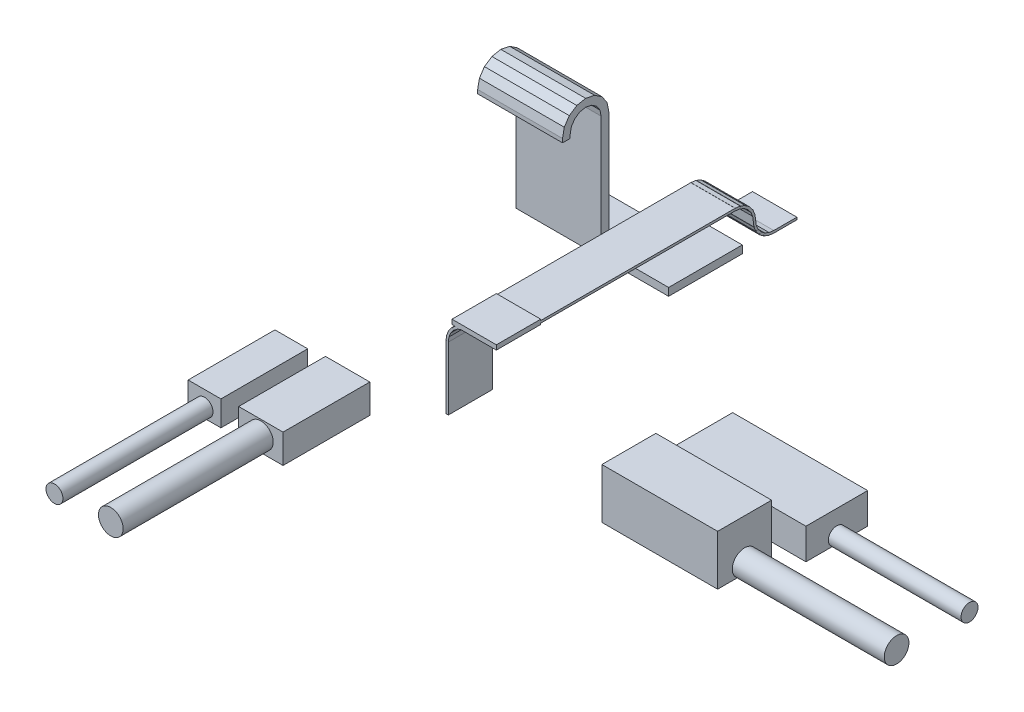
SolidWorks part; units mm, degrees
ref_plane "Front Plane" through (0, 0, 0) normal (0, 0, 1) x (1, 0, 0)
ref_plane "Top Plane" through (0, 0, 0) normal (0, 1, 0) x (1, 0, 0)
ref_plane "Right Plane" through (0, 0, 0) normal (1, 0, 0) x (0, 0, -1)
ref_plane "PY93" through (0, 0, 93) normal (0, 0, 1) x (1, 0, 0)
sketch "Sketch1" plane through (0, 0, 93) normal (0, 0, 1) x (1, 0, 0)
  line L0 (-48.05, -16.05) -> (-39.55, -16.05)
  line L1 (-39.55, -16.05) -> (-39.55, -9.55)
  line L2 (-39.55, -9.55) -> (-48.05, -9.55)
  line L3 (-48.05, -9.55) -> (-48.05, -16.05)
extrude "Plug usbc" add sketch "Sketch1" along normal blind 22.5
ref_plane "PY115" through (0, 0, 115) normal (0, 0, 1) x (1, 0, 0)
sketch "Sketch2" plane through (0, 0, 115) normal (0, 0, 1) x (1, 0, 0)
  circle A0 centre (-43.8, -13.5) radius 2.2
extrude "Cable usbc" add sketch "Sketch2" along normal blind 39.4
sketch "Sketch3" plane through (0, 0, 93) normal (0, 0, 1) x (1, 0, 0)
  line L0 (-34.95, -16.45) -> (-23.45, -16.45)
  line L1 (-23.45, -16.45) -> (-23.45, -8.95)
  line L2 (-23.45, -8.95) -> (-34.95, -8.95)
  line L3 (-34.95, -8.95) -> (-34.95, -16.45)
extrude "Plug hdmi" add sketch "Sketch3" along normal blind 22.5
sketch "Sketch4" plane through (0, 0, 115) normal (0, 0, 1) x (1, 0, 0)
  circle A0 centre (-29.2, -12.5) radius 3.2
extrude "Cable hdmi" add sketch "Sketch4" along normal blind 39.4
ref_plane "PX33" through (33, 0, 0) normal (1, 0, 0) x (0, 0, -1)
sketch "Sketch5" plane through (33, 0, 0) normal (1, 0, 0) x (0, 0, -1)
  line L0 (-89.3, -14.1) -> (-75.3, -14.1)
  line L1 (-75.3, -14.1) -> (-75.3, -1.1)
  line L2 (-75.3, -1.1) -> (-89.3, -1.1)
  line L3 (-89.3, -1.1) -> (-89.3, -14.1)
extrude "Plug eth" add sketch "Sketch5" along normal blind 30
ref_plane "PX62_5" through (62.5, 0, 0) normal (1, 0, 0) x (0, 0, -1)
sketch "Sketch6" plane through (62.5, 0, 0) normal (1, 0, 0) x (0, 0, -1)
  circle A0 centre (-82.3, -11.5) radius 3.2
extrude "Cable eth" add sketch "Sketch6" along normal blind 39.9
sketch "Sketch7" plane through (33, 0, 0) normal (1, 0, 0) x (0, 0, -1)
  line L0 (-71.4, -14.4) -> (-55.4, -14.4)
  line L1 (-55.4, -14.4) -> (-55.4, -6.4)
  line L2 (-55.4, -6.4) -> (-71.4, -6.4)
  line L3 (-71.4, -6.4) -> (-71.4, -14.4)
extrude "Plug usba" add sketch "Sketch7" along normal blind 35
ref_plane "PX67_5" through (67.5, 0, 0) normal (1, 0, 0) x (0, 0, -1)
sketch "Sketch8" plane through (67.5, 0, 0) normal (1, 0, 0) x (0, 0, -1)
  circle A0 centre (-63.4, -12.5) radius 2.2
extrude "Cable usba" add sketch "Sketch8" along normal blind 34.9
ref_plane "PXm5_35" through (-5.35, 0, 0) normal (1, 0, 0) x (0, 0, -1)
sketch "Sketch9" plane through (-5.35, 0, 0) normal (1, 0, 0) x (0, 0, -1)
  line L0 (-11.9, 1.7) -> (-17.9, 1.7)
  line L1 (-17.9, 1.7) -> (-17.9, 2.3)
  line L2 (-17.9, 2.3) -> (-11.9, 2.3)
  line L3 (-11.9, 2.3) -> (-11.9, 1.7)
extrude "Ribbon 0" add sketch "Sketch9" along normal blind 11.5
sketch "Sketch10" plane through (-5.35, 0, 0) normal (1, 0, 0) x (0, 0, -1)
  line L0 (-17.9392, 1.7026) -> (-19.2333, 1.8729)
  line L1 (-19.2333, 1.8729) -> (-19.1549, 2.4678)
  line L2 (-19.1549, 2.4678) -> (-17.8608, 2.2974)
  line L3 (-17.8608, 2.2974) -> (-17.9392, 1.7026)
extrude "Ribbon 1" add sketch "Sketch10" along normal blind 11.5
sketch "Sketch11" plane through (-5.35, 0, 0) normal (1, 0, 0) x (0, 0, -1)
  line L0 (-19.3089, 1.8932) -> (-20.5148, 2.3927)
  line L1 (-20.5148, 2.3927) -> (-20.2852, 2.947)
  line L2 (-20.2852, 2.947) -> (-19.0793, 2.4475)
  line L3 (-19.0793, 2.4475) -> (-19.3089, 1.8932)
extrude "Ribbon 2" add sketch "Sketch11" along normal blind 11.5
sketch "Sketch12" plane through (-5.35, 0, 0) normal (1, 0, 0) x (0, 0, -1)
  line L0 (-20.5826, 2.4319) -> (-21.6182, 3.2265)
  line L1 (-21.6182, 3.2265) -> (-21.2529, 3.7025)
  line L2 (-21.2529, 3.7025) -> (-20.2174, 2.9079)
  line L3 (-20.2174, 2.9079) -> (-20.5826, 2.4319)
extrude "Ribbon 3" add sketch "Sketch12" along normal blind 11.5
sketch "Sketch13" plane through (-5.35, 0, 0) normal (1, 0, 0) x (0, 0, -1)
  line L0 (-21.6735, 3.2818) -> (-22.4681, 4.3174)
  line L1 (-22.4681, 4.3174) -> (-21.9921, 4.6826)
  line L2 (-21.9921, 4.6826) -> (-21.1975, 3.6471)
  line L3 (-21.1975, 3.6471) -> (-21.6735, 3.2818)
extrude "Ribbon 4" add sketch "Sketch13" along normal blind 11.5
sketch "Sketch14" plane through (-5.35, 0, 0) normal (1, 0, 0) x (0, 0, -1)
  line L0 (-22.5073, 4.3852) -> (-23.0068, 5.5911)
  line L1 (-23.0068, 5.5911) -> (-22.4525, 5.8207)
  line L2 (-22.4525, 5.8207) -> (-21.953, 4.6148)
  line L3 (-21.953, 4.6148) -> (-22.5073, 4.3852)
extrude "Ribbon 5" add sketch "Sketch14" along normal blind 11.5
sketch "Sketch15" plane through (-5.35, 0, 0) normal (1, 0, 0) x (0, 0, -1)
  line L0 (-23.0271, 5.6667) -> (-23.1974, 6.9608)
  line L1 (-23.1974, 6.9608) -> (-22.6026, 7.0392)
  line L2 (-22.6026, 7.0392) -> (-22.4322, 5.7451)
  line L3 (-22.4322, 5.7451) -> (-23.0271, 5.6667)
extrude "Ribbon 6" add sketch "Sketch15" along normal blind 11.5
sketch "Sketch16" plane through (-5.35, 0, 0) normal (1, 0, 0) x (0, 0, -1)
  line L0 (-23.1974, 6.9608) -> (-23.3678, 8.2549)
  line L1 (-23.3678, 8.2549) -> (-22.7729, 8.3333)
  line L2 (-22.7729, 8.3333) -> (-22.6026, 7.0392)
  line L3 (-22.6026, 7.0392) -> (-23.1974, 6.9608)
extrude "Ribbon 7" add sketch "Sketch16" along normal blind 11.5
sketch "Sketch17" plane through (-5.35, 0, 0) normal (1, 0, 0) x (0, 0, -1)
  line L0 (-23.3475, 8.1793) -> (-23.847, 9.3852)
  line L1 (-23.847, 9.3852) -> (-23.2927, 9.6148)
  line L2 (-23.2927, 9.6148) -> (-22.7932, 8.4089)
  line L3 (-22.7932, 8.4089) -> (-23.3475, 8.1793)
extrude "Ribbon 8" add sketch "Sketch17" along normal blind 11.5
sketch "Sketch18" plane through (-5.35, 0, 0) normal (1, 0, 0) x (0, 0, -1)
  line L0 (-23.8079, 9.3174) -> (-24.6025, 10.3529)
  line L1 (-24.6025, 10.3529) -> (-24.1265, 10.7182)
  line L2 (-24.1265, 10.7182) -> (-23.3319, 9.6826)
  line L3 (-23.3319, 9.6826) -> (-23.8079, 9.3174)
extrude "Ribbon 9" add sketch "Sketch18" along normal blind 11.5
sketch "Sketch19" plane through (-5.35, 0, 0) normal (1, 0, 0) x (0, 0, -1)
  line L0 (-24.5471, 10.2975) -> (-25.5826, 11.0921)
  line L1 (-25.5826, 11.0921) -> (-25.2174, 11.5681)
  line L2 (-25.2174, 11.5681) -> (-24.1818, 10.7735)
  line L3 (-24.1818, 10.7735) -> (-24.5471, 10.2975)
extrude "Ribbon 10" add sketch "Sketch19" along normal blind 11.5
sketch "Sketch20" plane through (-5.35, 0, 0) normal (1, 0, 0) x (0, 0, -1)
  line L0 (-25.5148, 11.053) -> (-26.7207, 11.5525)
  line L1 (-26.7207, 11.5525) -> (-26.4911, 12.1068)
  line L2 (-26.4911, 12.1068) -> (-25.2852, 11.6073)
  line L3 (-25.2852, 11.6073) -> (-25.5148, 11.053)
extrude "Ribbon 11" add sketch "Sketch20" along normal blind 11.5
sketch "Sketch21" plane through (-5.35, 0, 0) normal (1, 0, 0) x (0, 0, -1)
  line L0 (-26.6451, 11.5322) -> (-27.9392, 11.7026)
  line L1 (-27.9392, 11.7026) -> (-27.8608, 12.2974)
  line L2 (-27.8608, 12.2974) -> (-26.5667, 12.1271)
  line L3 (-26.5667, 12.1271) -> (-26.6451, 11.5322)
extrude "Ribbon 12" add sketch "Sketch21" along normal blind 11.5
sketch "Sketch22" plane through (-5.35, 0, 0) normal (1, 0, 0) x (0, 0, -1)
  line L0 (-27.9, 11.7) -> (-84.05, 11.7)
  line L1 (-84.05, 11.7) -> (-84.05, 12.3)
  line L2 (-84.05, 12.3) -> (-27.9, 12.3)
  line L3 (-27.9, 12.3) -> (-27.9, 11.7)
extrude "Ribbon 13" add sketch "Sketch22" along normal blind 11.5
ref_plane "PZ11_4" through (0, 11.4, 0) normal (0, 1, 0) x (1, 0, 0)
sketch "Sketch23" plane through (0, 11.4, 0) normal (0, 1, 0) x (1, 0, 0)
  line L0 (-5.35, -89.8) -> (6.15, -89.8)
  line L1 (6.15, -89.8) -> (6.15, -78.3)
  line L2 (6.15, -78.3) -> (-5.35, -78.3)
  line L3 (-5.35, -78.3) -> (-5.35, -89.8)
extrude "Ribbon Fold" add sketch "Sketch23" along normal blind 1.2
ref_plane "PY78_3" through (0, 0, 78.3) normal (0, 0, 1) x (1, 0, 0)
sketch "Sketch24" plane through (0, 0, 78.3) normal (0, 0, 1) x (1, 0, 0)
  line L0 (0.4, 11.7) -> (-1.6, 11.7)
  line L1 (-1.6, 11.7) -> (-1.6, 12.3)
  line L2 (-1.6, 12.3) -> (0.4, 12.3)
  line L3 (0.4, 12.3) -> (0.4, 11.7)
extrude "Ribbon 14" add sketch "Sketch24" along normal blind 11.5
sketch "Sketch25" plane through (0, 0, 78.3) normal (0, 0, 1) x (1, 0, 0)
  line L0 (-1.5608, 11.7026) -> (-2.8549, 11.5322)
  line L1 (-2.8549, 11.5322) -> (-2.9333, 12.1271)
  line L2 (-2.9333, 12.1271) -> (-1.6392, 12.2974)
  line L3 (-1.6392, 12.2974) -> (-1.5608, 11.7026)
extrude "Ribbon 15" add sketch "Sketch25" along normal blind 11.5
sketch "Sketch26" plane through (0, 0, 78.3) normal (0, 0, 1) x (1, 0, 0)
  line L0 (-2.7793, 11.5525) -> (-3.9852, 11.053)
  line L1 (-3.9852, 11.053) -> (-4.2148, 11.6073)
  line L2 (-4.2148, 11.6073) -> (-3.0089, 12.1068)
  line L3 (-3.0089, 12.1068) -> (-2.7793, 11.5525)
extrude "Ribbon 16" add sketch "Sketch26" along normal blind 11.5
sketch "Sketch27" plane through (0, 0, 78.3) normal (0, 0, 1) x (1, 0, 0)
  line L0 (-3.9174, 11.0921) -> (-4.9529, 10.2975)
  line L1 (-4.9529, 10.2975) -> (-5.3182, 10.7735)
  line L2 (-5.3182, 10.7735) -> (-4.2826, 11.5681)
  line L3 (-4.2826, 11.5681) -> (-3.9174, 11.0921)
extrude "Ribbon 17" add sketch "Sketch27" along normal blind 11.5
sketch "Sketch28" plane through (0, 0, 78.3) normal (0, 0, 1) x (1, 0, 0)
  line L0 (-4.8975, 10.3529) -> (-5.6921, 9.3174)
  line L1 (-5.6921, 9.3174) -> (-6.1681, 9.6826)
  line L2 (-6.1681, 9.6826) -> (-5.3735, 10.7182)
  line L3 (-5.3735, 10.7182) -> (-4.8975, 10.3529)
extrude "Ribbon 18" add sketch "Sketch28" along normal blind 11.5
sketch "Sketch29" plane through (0, 0, 78.3) normal (0, 0, 1) x (1, 0, 0)
  line L0 (-5.653, 9.3852) -> (-6.1525, 8.1793)
  line L1 (-6.1525, 8.1793) -> (-6.7068, 8.4089)
  line L2 (-6.7068, 8.4089) -> (-6.2073, 9.6148)
  line L3 (-6.2073, 9.6148) -> (-5.653, 9.3852)
extrude "Ribbon 19" add sketch "Sketch29" along normal blind 11.5
sketch "Sketch30" plane through (0, 0, 78.3) normal (0, 0, 1) x (1, 0, 0)
  line L0 (-6.1322, 8.2549) -> (-6.3026, 6.9608)
  line L1 (-6.3026, 6.9608) -> (-6.8974, 7.0392)
  line L2 (-6.8974, 7.0392) -> (-6.7271, 8.3333)
  line L3 (-6.7271, 8.3333) -> (-6.1322, 8.2549)
extrude "Ribbon 20" add sketch "Sketch30" along normal blind 11.5
sketch "Sketch31" plane through (0, 0, 78.3) normal (0, 0, 1) x (1, 0, 0)
  line L0 (-6.3, 7) -> (-6.3, -9.39)
  line L1 (-6.3, -9.39) -> (-6.9, -9.39)
  line L2 (-6.9, -9.39) -> (-6.9, 7)
  line L3 (-6.9, 7) -> (-6.3, 7)
extrude "Ribbon 21" add sketch "Sketch31" along normal blind 11.5
ref_plane "PZm13" through (0, -13, 0) normal (0, 1, 0) x (1, 0, 0)
sketch "Sketch32" plane through (0, -13, 0) normal (0, 1, 0) x (1, 0, 0)
  line L0 (-18, -17.9) -> (-8, -17.9)
  line L1 (-8, -17.9) -> (-8, -11.9)
  line L2 (-8, -11.9) -> (-18, -11.9)
  line L3 (-18, -11.9) -> (-18, -17.9)
extrude "Jumpers Window" add sketch "Sketch32" along normal blind 2
sketch "Sketch33" plane through (0, -13, 0) normal (0, 1, 0) x (1, 0, 0)
  line L0 (-47.5, -31) -> (-8, -31)
  line L1 (-8, -31) -> (-8, -17.9)
  line L2 (-8, -17.9) -> (-47.5, -17.9)
  line L3 (-47.5, -17.9) -> (-47.5, -31)
extrude "Jumpers Across" add sketch "Sketch33" along normal blind 2
ref_plane "PXm47_5" through (-47.5, 0, 0) normal (1, 0, 0) x (0, 0, -1)
sketch "Sketch34" plane through (-47.5, 0, 0) normal (1, 0, 0) x (0, 0, -1)
  line L0 (-31, -13) -> (-29, -13)
  line L1 (-29, -13) -> (-29, 18.7)
  line L2 (-29, 18.7) -> (-31, 18.7)
  line L3 (-31, 18.7) -> (-31, -13)
extrude "Jumpers Rise" add sketch "Sketch34" along normal blind 22
sketch "Sketch35" plane through (-47.5, 0, 0) normal (1, 0, 0) x (0, 0, -1)
  line L0 (-29, 18.7) -> (-29.4567, 20.9961)
  line L1 (-29.4567, 20.9961) -> (-30.7574, 22.9426)
  line L2 (-30.7574, 22.9426) -> (-32.7039, 24.2433)
  line L3 (-32.7039, 24.2433) -> (-35, 24.7)
  line L4 (-35, 24.7) -> (-37.2961, 24.2433)
  line L5 (-37.2961, 24.2433) -> (-39.2426, 22.9426)
  line L6 (-39.2426, 22.9426) -> (-40.5433, 20.9961)
  line L7 (-40.5433, 20.9961) -> (-41, 18.7)
  line L8 (-41, 18.7) -> (-39, 18.7)
  line L9 (-39, 18.7) -> (-38.6955, 20.2307)
  line L10 (-38.6955, 20.2307) -> (-37.8284, 21.5284)
  line L11 (-37.8284, 21.5284) -> (-36.5307, 22.3955)
  line L12 (-36.5307, 22.3955) -> (-35, 22.7)
  line L13 (-35, 22.7) -> (-33.4693, 22.3955)
  line L14 (-33.4693, 22.3955) -> (-32.1716, 21.5284)
  line L15 (-32.1716, 21.5284) -> (-31.3045, 20.2307)
  line L16 (-31.3045, 20.2307) -> (-31, 18.7)
  line L17 (-31, 18.7) -> (-29, 18.7)
extrude "Jumpers Hairpin" add sketch "Sketch35" along normal blind 22
sketch "Sketch36" plane through (-47.5, 0, 0) normal (1, 0, 0) x (0, 0, -1)
  line L0 (-41, 17.71) -> (-39, 17.71)
  line L1 (-39, 17.71) -> (-39, 18.7)
  line L2 (-39, 18.7) -> (-41, 18.7)
  line L3 (-41, 18.7) -> (-41, 17.71)
extrude "Jumpers Into Housings" add sketch "Sketch36" along normal blind 22
